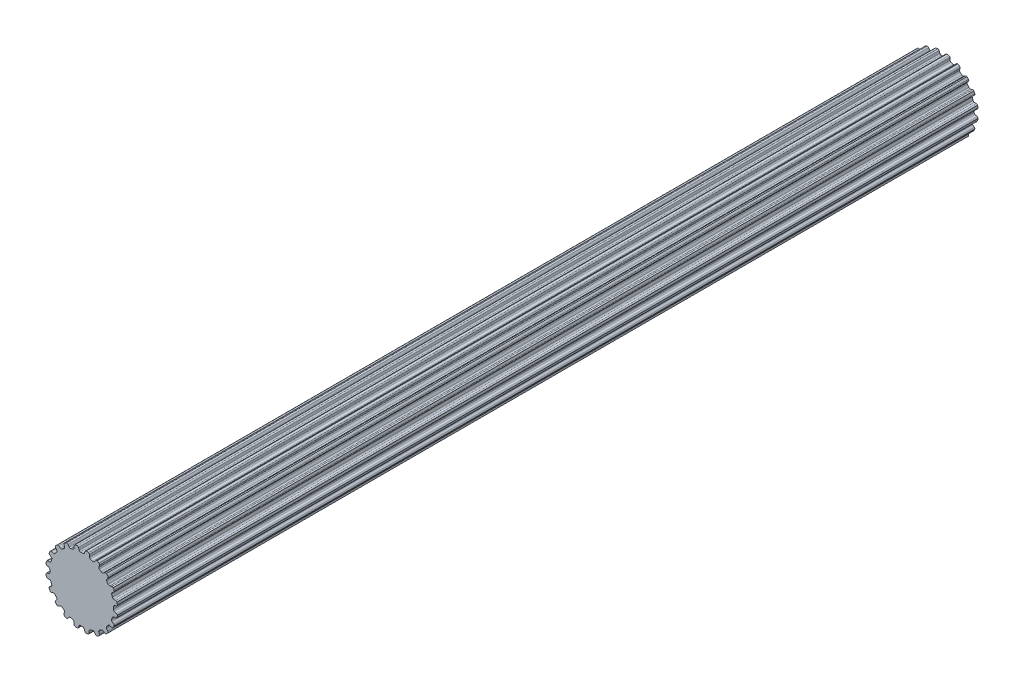
SolidWorks part; units mm, degrees
ref_plane "Front Plane" through (0, 0, 0) normal (0, 0, 1) x (1, 0, 0)
ref_plane "Top Plane" through (0, 0, 0) normal (0, 1, 0) x (1, 0, 0)
ref_plane "Right Plane" through (0, 0, 0) normal (1, 0, 0) x (0, 0, -1)
sketch "Sketch1" plane through (0, 0, 0) normal (0, 0, 1) x (1, 0, 0)
  line L0 (-0.1069, 2.9699) -> (0.1069, 2.9699)
  line L1 (0.3159, 3.2375) -> (0.2537, 3.0575)
  line L2 (-0.2964, 3.2367) -> (-0.2318, 3.0575)
  line L3 (-0.2964, 3.2367) -> (0.3159, 3.2375) construction
  line L4 (0, 3.3252) -> (0, 0) construction
  line L5 (-0.2318, 3.0575) -> (0.2537, 3.0575) construction
  line L6 (-0.4281, 3.3241) -> (0.4281, 3.3263) construction
  line L7 (0.7183, 3.1698) -> (0.7244, 2.9795)
  line L8 (0.816, 2.8576) -> (1.0195, 2.7915)
  line L9 (1.3009, 2.9815) -> (1.1862, 2.8295)
  line L10 (1.6627, 2.7927) -> (1.6097, 2.6099)
  line L11 (1.6591, 2.4655) -> (1.8322, 2.3398)
  line L12 (2.1585, 2.4335) -> (2.0025, 2.3245)
  line L13 (2.4443, 2.1423) -> (2.3374, 1.9847)
  line L14 (2.3398, 1.8322) -> (2.4655, 1.6591)
  line L15 (2.8049, 1.6474) -> (2.6228, 1.5919)
  line L16 (2.9866, 1.2821) -> (2.8363, 1.1653)
  line L17 (2.7915, 1.0195) -> (2.8576, 0.816)
  line L18 (3.1767, 0.7) -> (2.9863, 0.7035)
  line L19 (3.2367, 0.2964) -> (3.0575, 0.2318)
  line L20 (2.9699, 0.1069) -> (2.9699, -0.1069)
  line L21 (3.2375, -0.3159) -> (3.0575, -0.2537)
  line L22 (3.1698, -0.7183) -> (2.9795, -0.7244)
  line L23 (2.8576, -0.816) -> (2.7915, -1.0195)
  line L24 (2.9815, -1.3009) -> (2.8295, -1.1862)
  line L25 (2.7927, -1.6627) -> (2.6099, -1.6097)
  line L26 (2.4655, -1.6591) -> (2.3398, -1.8322)
  line L27 (2.4335, -2.1585) -> (2.3245, -2.0025)
  line L28 (2.1423, -2.4443) -> (1.9847, -2.3374)
  line L29 (1.8322, -2.3398) -> (1.6591, -2.4655)
  line L30 (1.6474, -2.8049) -> (1.5919, -2.6228)
  line L31 (1.2821, -2.9866) -> (1.1653, -2.8363)
  line L32 (1.0195, -2.7915) -> (0.816, -2.8576)
  line L33 (0.7, -3.1767) -> (0.7035, -2.9863)
  line L34 (0.2964, -3.2367) -> (0.2318, -3.0575)
  line L35 (0.1069, -2.9699) -> (-0.1069, -2.9699)
  line L36 (-0.3159, -3.2375) -> (-0.2537, -3.0575)
  line L37 (-0.7183, -3.1698) -> (-0.7244, -2.9795)
  line L38 (-0.816, -2.8576) -> (-1.0195, -2.7915)
  line L39 (-1.3009, -2.9815) -> (-1.1862, -2.8295)
  line L40 (-1.6627, -2.7927) -> (-1.6097, -2.6099)
  line L41 (-1.6591, -2.4655) -> (-1.8322, -2.3398)
  line L42 (-2.1585, -2.4335) -> (-2.0025, -2.3245)
  line L43 (-2.4443, -2.1423) -> (-2.3374, -1.9847)
  line L44 (-2.3398, -1.8322) -> (-2.4655, -1.6591)
  line L45 (-2.8049, -1.6474) -> (-2.6228, -1.5919)
  line L46 (-2.9866, -1.2821) -> (-2.8363, -1.1653)
  line L47 (-2.7915, -1.0195) -> (-2.8576, -0.816)
  line L48 (-3.1767, -0.7) -> (-2.9863, -0.7035)
  line L49 (-3.2367, -0.2964) -> (-3.0575, -0.2318)
  line L50 (-2.9699, -0.1069) -> (-2.9699, 0.1069)
  line L51 (-3.2375, 0.3159) -> (-3.0575, 0.2537)
  line L52 (-3.1698, 0.7183) -> (-2.9795, 0.7244)
  line L53 (-2.8576, 0.816) -> (-2.7915, 1.0195)
  line L54 (-2.9815, 1.3009) -> (-2.8295, 1.1862)
  line L55 (-2.7927, 1.6627) -> (-2.6099, 1.6097)
  line L56 (-2.4655, 1.6591) -> (-2.3398, 1.8322)
  line L57 (-2.4335, 2.1585) -> (-2.3245, 2.0025)
  line L58 (-2.1423, 2.4443) -> (-1.9847, 2.3374)
  line L59 (-1.8322, 2.3398) -> (-1.6591, 2.4655)
  line L60 (-1.6474, 2.8049) -> (-1.5919, 2.6228)
  line L61 (-1.2821, 2.9866) -> (-1.1653, 2.8363)
  line L62 (-1.0195, 2.7915) -> (-0.816, 2.8576)
  line L63 (-0.7, 3.1767) -> (-0.7035, 2.9863)
  line L64 (0.4281, 3.3263) -> (0.62, 3.2938)
  line L65 (1.4351, 3.0312) -> (1.6075, 2.9409)
  line L66 (2.3015, 2.4394) -> (2.4376, 2.3003)
  line L67 (2.9427, 1.6088) -> (3.0291, 1.4344)
  line L68 (3.2958, 0.6207) -> (3.3241, 0.4281)
  line L69 (3.3263, -0.4281) -> (3.2938, -0.62)
  line L70 (3.0312, -1.4351) -> (2.9409, -1.6075)
  line L71 (2.4394, -2.3015) -> (2.3003, -2.4376)
  line L72 (1.6088, -2.9427) -> (1.4344, -3.0291)
  line L73 (0.6207, -3.2958) -> (0.4281, -3.3241)
  line L74 (-0.4281, -3.3263) -> (-0.62, -3.2938)
  line L75 (-1.4351, -3.0312) -> (-1.6075, -2.9409)
  line L76 (-2.3015, -2.4394) -> (-2.4376, -2.3003)
  line L77 (-2.9427, -1.6088) -> (-3.0291, -1.4344)
  line L78 (-3.2958, -0.6207) -> (-3.3241, -0.4281)
  line L79 (-3.3263, 0.4281) -> (-3.2938, 0.62)
  line L80 (-3.0312, 1.4351) -> (-2.9409, 1.6075)
  line L81 (-2.4394, 2.3015) -> (-2.3003, 2.4376)
  line L82 (-1.6088, 2.9427) -> (-1.4344, 3.0291)
  line L83 (-0.6207, 3.2958) -> (-0.4281, 3.3241)
  arc A0 (0.2537, 3.0575) -> (0.1069, 2.9699) centre (0.1283, 3.1009) cw
  arc A1 (-0.2318, 3.0575) -> (-0.1069, 2.9699) centre (-0.1069, 3.1026) ccw
  arc A2 (0.62, 3.2938) -> (0.7183, 3.1698) centre (0.5856, 3.1656) cw
  arc A3 (0.7244, 2.9795) -> (0.816, 2.8576) centre (0.857, 2.9838) ccw
  arc A4 (-0.4281, 3.3241) -> (-0.2964, 3.2367) centre (-0.4213, 3.1916) cw
  arc A5 (0.4281, 3.3263) -> (0.3159, 3.2375) centre (0.4413, 3.1942) ccw
  arc A6 (1.1862, 2.8295) -> (1.0195, 2.7915) centre (1.0802, 2.9095) cw
  arc A7 (1.4351, 3.0312) -> (1.3009, 2.9815) centre (1.4068, 2.9015) ccw
  arc A8 (1.6075, 2.9409) -> (1.6627, 2.7927) centre (1.5352, 2.8297) cw
  arc A9 (1.6097, 2.6099) -> (1.6591, 2.4655) centre (1.7371, 2.5729) ccw
  arc A10 (2.0025, 2.3245) -> (1.8322, 2.3398) centre (1.9264, 2.4332) cw
  arc A11 (2.3015, 2.4394) -> (2.1585, 2.4335) centre (2.2346, 2.3248) ccw
  arc A12 (2.4376, 2.3003) -> (2.4443, 2.1423) centre (2.3345, 2.2168) cw
  arc A13 (2.3374, 1.9847) -> (2.3398, 1.8322) centre (2.4472, 1.9102) ccw
  arc A14 (2.6228, 1.5919) -> (2.4655, 1.6591) centre (2.5841, 1.7189) cw
  arc A15 (2.9427, 1.6088) -> (2.8049, 1.6474) centre (2.8436, 1.5205) ccw
  arc A16 (3.0291, 1.4344) -> (2.9866, 1.2821) centre (2.9052, 1.3869) cw
  arc A17 (2.8363, 1.1653) -> (2.7915, 1.0195) centre (2.9177, 1.0605) ccw
  arc A18 (2.9863, 0.7035) -> (2.8576, 0.816) centre (2.9887, 0.8362) cw
  arc A19 (3.2958, 0.6207) -> (3.1767, 0.7) centre (3.1743, 0.5673) ccw
  arc A20 (3.3241, 0.4281) -> (3.2367, 0.2964) centre (3.1916, 0.4213) cw
  arc A21 (3.0575, 0.2318) -> (2.9699, 0.1069) centre (3.1026, 0.1069) ccw
  arc A22 (3.0575, -0.2537) -> (2.9699, -0.1069) centre (3.1009, -0.1283) cw
  arc A23 (3.3263, -0.4281) -> (3.2375, -0.3159) centre (3.1942, -0.4413) ccw
  arc A24 (3.2938, -0.62) -> (3.1698, -0.7183) centre (3.1656, -0.5856) cw
  arc A25 (2.9795, -0.7244) -> (2.8576, -0.816) centre (2.9838, -0.857) ccw
  arc A26 (2.8295, -1.1862) -> (2.7915, -1.0195) centre (2.9095, -1.0802) cw
  arc A27 (3.0312, -1.4351) -> (2.9815, -1.3009) centre (2.9015, -1.4068) ccw
  arc A28 (2.9409, -1.6075) -> (2.7927, -1.6627) centre (2.8297, -1.5352) cw
  arc A29 (2.6099, -1.6097) -> (2.4655, -1.6591) centre (2.5729, -1.7371) ccw
  arc A30 (2.3245, -2.0025) -> (2.3398, -1.8322) centre (2.4332, -1.9264) cw
  arc A31 (2.4394, -2.3015) -> (2.4335, -2.1585) centre (2.3248, -2.2346) ccw
  arc A32 (2.3003, -2.4376) -> (2.1423, -2.4443) centre (2.2168, -2.3345) cw
  arc A33 (1.9847, -2.3374) -> (1.8322, -2.3398) centre (1.9102, -2.4472) ccw
  arc A34 (1.5919, -2.6228) -> (1.6591, -2.4655) centre (1.7189, -2.5841) cw
  arc A35 (1.6088, -2.9427) -> (1.6474, -2.8049) centre (1.5205, -2.8436) ccw
  arc A36 (1.4344, -3.0291) -> (1.2821, -2.9866) centre (1.3869, -2.9052) cw
  arc A37 (1.1653, -2.8363) -> (1.0195, -2.7915) centre (1.0605, -2.9177) ccw
  arc A38 (0.7035, -2.9863) -> (0.816, -2.8576) centre (0.8362, -2.9887) cw
  arc A39 (0.6207, -3.2958) -> (0.7, -3.1767) centre (0.5673, -3.1743) ccw
  arc A40 (0.4281, -3.3241) -> (0.2964, -3.2367) centre (0.4213, -3.1916) cw
  arc A41 (0.2318, -3.0575) -> (0.1069, -2.9699) centre (0.1069, -3.1026) ccw
  arc A42 (-0.2537, -3.0575) -> (-0.1069, -2.9699) centre (-0.1283, -3.1009) cw
  arc A43 (-0.4281, -3.3263) -> (-0.3159, -3.2375) centre (-0.4413, -3.1942) ccw
  arc A44 (-0.62, -3.2938) -> (-0.7183, -3.1698) centre (-0.5856, -3.1656) cw
  arc A45 (-0.7244, -2.9795) -> (-0.816, -2.8576) centre (-0.857, -2.9838) ccw
  arc A46 (-1.1862, -2.8295) -> (-1.0195, -2.7915) centre (-1.0802, -2.9095) cw
  arc A47 (-1.4351, -3.0312) -> (-1.3009, -2.9815) centre (-1.4068, -2.9015) ccw
  arc A48 (-1.6075, -2.9409) -> (-1.6627, -2.7927) centre (-1.5352, -2.8297) cw
  arc A49 (-1.6097, -2.6099) -> (-1.6591, -2.4655) centre (-1.7371, -2.5729) ccw
  arc A50 (-2.0025, -2.3245) -> (-1.8322, -2.3398) centre (-1.9264, -2.4332) cw
  arc A51 (-2.3015, -2.4394) -> (-2.1585, -2.4335) centre (-2.2346, -2.3248) ccw
  arc A52 (-2.4376, -2.3003) -> (-2.4443, -2.1423) centre (-2.3345, -2.2168) cw
  arc A53 (-2.3374, -1.9847) -> (-2.3398, -1.8322) centre (-2.4472, -1.9102) ccw
  arc A54 (-2.6228, -1.5919) -> (-2.4655, -1.6591) centre (-2.5841, -1.7189) cw
  arc A55 (-2.9427, -1.6088) -> (-2.8049, -1.6474) centre (-2.8436, -1.5205) ccw
  arc A56 (-3.0291, -1.4344) -> (-2.9866, -1.2821) centre (-2.9052, -1.3869) cw
  arc A57 (-2.8363, -1.1653) -> (-2.7915, -1.0195) centre (-2.9177, -1.0605) ccw
  arc A58 (-2.9863, -0.7035) -> (-2.8576, -0.816) centre (-2.9887, -0.8362) cw
  arc A59 (-3.2958, -0.6207) -> (-3.1767, -0.7) centre (-3.1743, -0.5673) ccw
  arc A60 (-3.3241, -0.4281) -> (-3.2367, -0.2964) centre (-3.1916, -0.4213) cw
  arc A61 (-3.0575, -0.2318) -> (-2.9699, -0.1069) centre (-3.1026, -0.1069) ccw
  arc A62 (-3.0575, 0.2537) -> (-2.9699, 0.1069) centre (-3.1009, 0.1283) cw
  arc A63 (-3.3263, 0.4281) -> (-3.2375, 0.3159) centre (-3.1942, 0.4413) ccw
  arc A64 (-3.2938, 0.62) -> (-3.1698, 0.7183) centre (-3.1656, 0.5856) cw
  arc A65 (-2.9795, 0.7244) -> (-2.8576, 0.816) centre (-2.9838, 0.857) ccw
  arc A66 (-2.8295, 1.1862) -> (-2.7915, 1.0195) centre (-2.9095, 1.0802) cw
  arc A67 (-3.0312, 1.4351) -> (-2.9815, 1.3009) centre (-2.9015, 1.4068) ccw
  arc A68 (-2.9409, 1.6075) -> (-2.7927, 1.6627) centre (-2.8297, 1.5352) cw
  arc A69 (-2.6099, 1.6097) -> (-2.4655, 1.6591) centre (-2.5729, 1.7371) ccw
  arc A70 (-2.3245, 2.0025) -> (-2.3398, 1.8322) centre (-2.4332, 1.9264) cw
  arc A71 (-2.4394, 2.3015) -> (-2.4335, 2.1585) centre (-2.3248, 2.2346) ccw
  arc A72 (-2.3003, 2.4376) -> (-2.1423, 2.4443) centre (-2.2168, 2.3345) cw
  arc A73 (-1.9847, 2.3374) -> (-1.8322, 2.3398) centre (-1.9102, 2.4472) ccw
  arc A74 (-1.5919, 2.6228) -> (-1.6591, 2.4655) centre (-1.7189, 2.5841) cw
  arc A75 (-1.6088, 2.9427) -> (-1.6474, 2.8049) centre (-1.5205, 2.8436) ccw
  arc A76 (-1.4344, 3.0291) -> (-1.2821, 2.9866) centre (-1.3869, 2.9052) cw
  arc A77 (-1.1653, 2.8363) -> (-1.0195, 2.7915) centre (-1.0605, 2.9177) ccw
  arc A78 (-0.7035, 2.9863) -> (-0.816, 2.8576) centre (-0.8362, 2.9887) cw
  arc A79 (-0.6207, 3.2958) -> (-0.7, 3.1767) centre (-0.5673, 3.1743) ccw
  point P14 (0, 2.9699)
  point P247 (0, 0)
  dimension "D4" = 0.1327
  dimension "D8" = 20
  dimension "D1" = 2.9699
  dimension "D2" = 0.2139
  dimension "D3" = 0.1904
  dimension "D5" = 0.0877
  dimension "D6" = 0.4855
  dimension "D7" = 0.8563
extrude "Boss-Extrude1" add sketch "Sketch1" along normal mid plane 80.231
sketch "Sketch2" plane through (0, 0, 40.1155) normal (0, 0, 1) x (1, 0, 0)
  circle A0 centre (0, 0) radius 3.3516 construction
sketch "Sketch3" plane through (0, 0, -40.1155) normal (0, 0, -1) x (-1, 0, 0)
  circle A0 centre (0, 0) radius 3.3516 construction
  circle A1 centre (0, 0) radius 3.3516 construction
sketch "Sketch4" plane through (0, 0, 0) normal (1, 0, 0) x (0, 0, -1)
  line L0 (40.1155, 0) -> (-40.1155, 0) construction
  line L2 (0, 9.7112) -> (0, -9.7112) construction
  point P6 (0, 0)
sketch "Sketch6" plane through (0, 0, 0) normal (0, 1, 0) x (1, 0, 0)
  line L0 (13.3396, 0) -> (-13.3396, 0) construction
  line L1 (0, 40.1155) -> (0, -40.1155) construction
